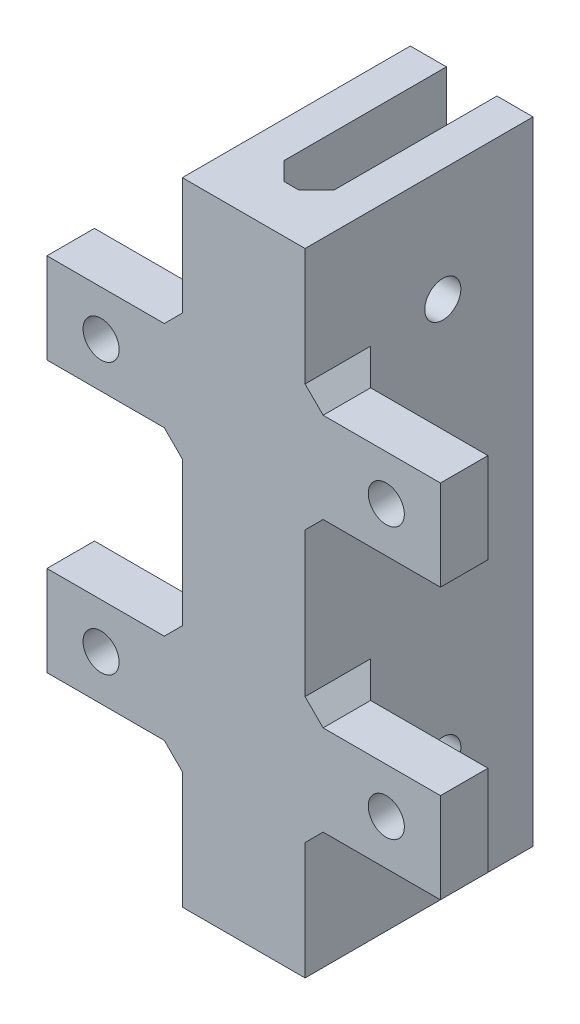
SolidWorks part; units mm, degrees
ref_plane "Front Plane" through (0, 0, 0) normal (0, 0, 1) x (1, 0, 0)
ref_plane "Top Plane" through (0, 0, 0) normal (0, 1, 0) x (1, 0, 0)
ref_plane "Right Plane" through (0, 0, 0) normal (1, 0, 0) x (0, 0, -1)
sketch "Sketch1" plane through (0, 0, 0) normal (0, 1, 0) x (1, 0, 0)
  line L0 (0, 0) -> (-23.0109, 0) construction
  line L1 (5.5709, 0) -> (5.5709, -19.5266) construction
  line L2 (-16.2291, 0) -> (-1.2291, 0)
  line L3 (-1.2291, 0) -> (-1.2291, 20)
  line L4 (-1.2291, 20) -> (2.7709, 20)
  line L5 (2.7709, 20) -> (2.7709, 0)
  line L6 (2.7709, 0) -> (8.3709, 0)
  line L7 (8.3709, 20) -> (8.3709, 0)
  line L8 (12.3709, 20) -> (8.3709, 20)
  line L9 (12.3709, 0) -> (12.3709, 20)
  line L10 (27.3709, 0) -> (12.3709, 0)
  line L11 (-16.2291, 0) -> (-16.2291, -5.2612)
  line L12 (-16.2291, -5.2612) -> (27.3709, -5.2612)
  line L13 (27.3709, -5.2612) -> (27.3709, 0)
  dimension "D1" = 2.8
  dimension "D2" = 20
  dimension "D3" = 4
  dimension "D4" = 15
extrude "Boss-Extrude1" add sketch "Sketch1" along normal blind 70
sketch "Sketch2" plane through (0, 0, 0) normal (0, 0, -1) x (-1, 0, 0)
  line L0 (-12.3709, 35) -> (1.2291, 35) construction
  line L1 (-27.3709, 70) -> (-27.3709, 0) construction
  line L2 (-21.3709, 55) -> (-21.3709, 45) construction
  line L3 (-5.5709, 70) -> (-5.5709, 0) construction
  line L4 (-8.3709, 70) -> (-2.7709, 70) construction
  line L5 (-8.3709, 0) -> (-2.7709, 0) construction
  line L6 (-12.3709, 70) -> (-12.3709, 0) construction
  line L7 (-27.3709, 70) -> (-12.3709, 70)
  line L8 (-27.3709, 70) -> (-27.3709, 55)
  line L9 (-27.3709, 55) -> (-12.3709, 55)
  line L10 (-12.3709, 70) -> (-12.3709, 55)
  line L13 (-12.3709, 25) -> (-12.3709, 45)
  line L14 (-12.3709, 45) -> (-27.3709, 45)
  line L15 (-27.3709, 25) -> (-27.3709, 45)
  line L16 (16.2291, 25) -> (16.2291, 45)
  line L17 (1.2291, 25) -> (1.2291, 45)
  line L18 (1.2291, 45) -> (16.2291, 45)
  line L19 (16.2291, 70) -> (1.2291, 70)
  line L20 (1.2291, 70) -> (1.2291, 55)
  line L21 (16.2291, 55) -> (1.2291, 55)
  line L22 (16.2291, 70) -> (16.2291, 55)
  line L23 (16.2291, 0) -> (16.2291, 15)
  line L24 (16.2291, 15) -> (1.2291, 15)
  line L25 (1.2291, 0) -> (1.2291, 15)
  line L26 (16.2291, 0) -> (1.2291, 0)
  line L27 (1.2291, 25) -> (16.2291, 25)
  line L28 (-12.3709, 25) -> (-27.3709, 25)
  line L29 (-12.3709, 0) -> (-12.3709, 15)
  line L30 (-27.3709, 15) -> (-12.3709, 15)
  line L31 (-27.3709, 0) -> (-27.3709, 15)
  line L32 (-27.3709, 0) -> (-12.3709, 0)
  circle A0 centre (-21.3709, 50) radius 2
  circle A1 centre (10.2291, 50) radius 2
  circle A2 centre (10.2291, 20) radius 2
  circle A3 centre (-21.3709, 20) radius 2
  dimension "D3" = 4
  dimension "D1" = 15
  dimension "D2" = 6
extrude "Cut-Extrude1" cut sketch "Sketch2" against normal through all both and the other way through all
sketch "Sketch3" plane through (12.3709, 0, 0) normal (1, 0, 0) x (0, 0, -1)
  line L0 (10, 70) -> (10, 0) construction
  line L1 (-5.2612, 70) -> (20, 70) construction
  line L2 (-5.2612, 0) -> (20, 0) construction
  line L3 (20, 70) -> (20, 0) construction
  line L4 (10, 57.5) -> (20, 57.5) construction
  circle A0 centre (10, 57.5) radius 2
  circle A1 centre (10, 35.5) radius 2
  circle A2 centre (10, 13.5) radius 2
  dimension "D3" = 4
  dimension "D1" = 10
  dimension "D2" = 12.5
  dimension "D4" = 3
extrude "Cut-Extrude2" cut sketch "Sketch3" against normal through all both and the other way through all
chamfer "Chamfer1" distance 2 angle 45 14 edges at (-1.2291, 25, 2.6306) (-1.2291, 20, 0) (-1.2291, 15, 2.6306) (-1.2291, 45, 2.6306) (-1.2291, 50, 0) (-1.2291, 55, 2.6306) (12.3709, 55, 2.6306) (12.3709, 45, 2.6306) (12.3709, 50, 0) (12.3709, 15, 2.6306) (12.3709, 25, 2.6306) (12.3709, 20, 0) (2.7709, 35, 0) (8.3709, 35, 0)
